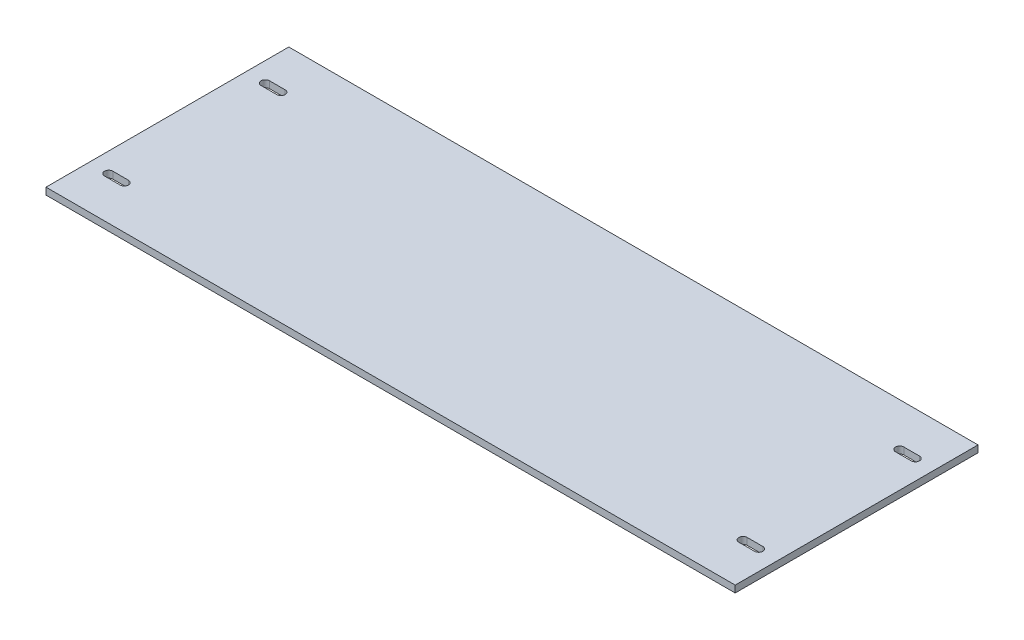
SolidWorks part; units mm, degrees
material "PC High Viscosity"
ref_plane "Front" through (0, 0, 0) normal (0, 0, 1) x (1, 0, 0)
ref_plane "Top" through (0, 0, 0) normal (0, 1, 0) x (1, 0, 0)
ref_plane "Right" through (0, 0, 0) normal (1, 0, 0) x (0, 0, -1)
sketch "Sketch1" plane through (0, 0, 0) normal (0, 1, 0) x (1, 0, 0)
  line L0 (15.875, 34.925) -> (28.575, 34.925) construction
  line L1 (0, 0) -> (558.8, 0)
  line L2 (0, 0) -> (0, 196.85)
  line L3 (0, 196.85) -> (558.8, 196.85)
  line L4 (558.8, 0) -> (558.8, 196.85)
  line L5 (15.875, 38.3032) -> (28.575, 38.3032)
  line L6 (15.875, 31.5468) -> (28.575, 31.5468)
  line L7 (22.225, 34.925) -> (22.225, 161.925) construction
  line L8 (15.875, 161.925) -> (28.575, 161.925) construction
  line L9 (15.875, 165.3032) -> (28.575, 165.3032)
  line L10 (15.875, 158.5468) -> (28.575, 158.5468)
  line L11 (22.225, 161.925) -> (66.675, 161.925) construction
  line L12 (66.675, 161.925) -> (66.675, 34.925) construction
  line L13 (66.675, 34.925) -> (22.225, 34.925) construction
  line L14 (60.325, 161.925) -> (73.025, 161.925) construction
  line L15 (60.325, 165.3032) -> (73.025, 165.3032) construction
  line L16 (60.325, 158.5468) -> (73.025, 158.5468) construction
  line L17 (60.325, 34.925) -> (73.025, 34.925) construction
  line L18 (60.325, 38.3032) -> (73.025, 38.3032) construction
  line L19 (60.325, 31.5468) -> (73.025, 31.5468) construction
  line L20 (536.575, 161.925) -> (536.575, 34.925) construction
  line L21 (542.925, 161.925) -> (530.225, 161.925) construction
  line L22 (542.925, 158.5468) -> (530.225, 158.5468)
  line L23 (542.925, 165.3032) -> (530.225, 165.3032)
  line L24 (542.925, 34.925) -> (530.225, 34.925) construction
  line L25 (542.925, 31.5468) -> (530.225, 31.5468)
  line L26 (542.925, 38.3032) -> (530.225, 38.3032)
  arc A0 (15.875, 38.3032) -> (15.875, 31.5468) centre (15.875, 34.925) ccw
  arc A1 (28.575, 31.5468) -> (28.575, 38.3032) centre (28.575, 34.925) ccw
  arc A2 (15.875, 165.3032) -> (15.875, 158.5468) centre (15.875, 161.925) ccw
  arc A3 (28.575, 158.5468) -> (28.575, 165.3032) centre (28.575, 161.925) ccw
  arc A4 (60.325, 165.3032) -> (60.325, 158.5468) centre (60.325, 161.925) ccw construction
  arc A5 (73.025, 158.5468) -> (73.025, 165.3032) centre (73.025, 161.925) ccw construction
  arc A6 (60.325, 38.3032) -> (60.325, 31.5468) centre (60.325, 34.925) ccw construction
  arc A7 (73.025, 31.5468) -> (73.025, 38.3032) centre (73.025, 34.925) ccw construction
  arc A8 (542.925, 158.5468) -> (542.925, 165.3032) centre (542.925, 161.925) ccw
  arc A9 (530.225, 165.3032) -> (530.225, 158.5468) centre (530.225, 161.925) ccw
  arc A10 (542.925, 31.5468) -> (542.925, 38.3032) centre (542.925, 34.925) ccw
  arc A11 (530.225, 38.3032) -> (530.225, 31.5468) centre (530.225, 34.925) ccw
  point P7 (22.225, 34.925)
  point P13 (22.225, 161.925)
  point P25 (66.675, 161.925)
  point P31 (66.675, 34.925)
  point P40 (536.575, 161.925)
  point P47 (536.575, 34.925)
  dimension "D1" = 6.7564
  dimension "D2" = 34.925
  dimension "D3" = 12.7
  dimension "D4" = 22.225
  dimension "D5" = 127
  dimension "D6" = 34.925
  dimension "D7" = 44.45
  dimension "D8" = 22.225
  dimension "D9" = 514.35
extrude "Boss-Extrude1" add sketch "Sketch1" along normal blind 5.588
fillet "Fillet1" [suppressed] radius 3.175
sketch "Sketch2" plane through (0, 5.588, 0) normal (0, 1, 0) x (1, 0, 0)
  line L0 (279.4, 196.85) -> (279.4, 0) construction
  line L1 (558.8, 196.85) -> (0, 196.85) construction
  line L2 (0, 0) -> (558.8, 0) construction
  line L4 (469.9, 25.4) -> (88.9, 25.4) construction
  line L5 (469.9, 25.4) -> (469.9, 171.45) construction
  line L6 (469.9, 171.45) -> (88.9, 171.45) construction
  line L7 (88.9, 25.4) -> (88.9, 171.45) construction
  line L8 (469.9, 25.4) -> (88.9, 171.45) construction
  line L9 (469.9, 171.45) -> (88.9, 25.4) construction
  circle A0 centre (88.9, 171.45) radius 3.3782
  circle A1 centre (88.9, 25.4) radius 3.3782
  circle A2 centre (469.9, 25.4) radius 3.3782
  circle A3 centre (469.9, 171.45) radius 3.3782
  point P6 (279.4, 98.425)
  dimension "D3" = 6.7564
  dimension "D1" = 25.4
  dimension "D2" = 381
extrude "Cut-Extrude1" [suppressed] cut sketch "Sketch2" against normal through all
